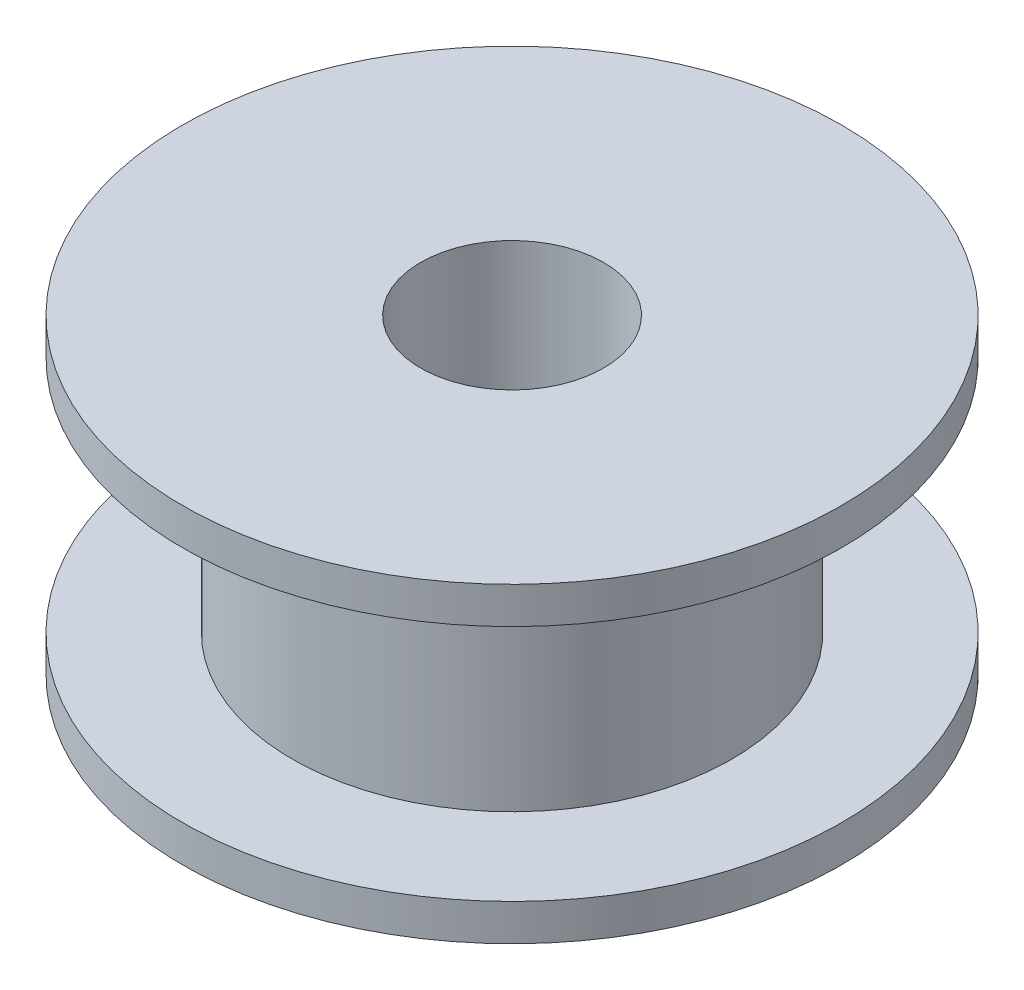
SolidWorks part; units mm, degrees
material "1060 slitina"
ref_plane "Přední rovina" through (0, 0, 0) normal (0, 0, 1) x (1, 0, 0)
ref_plane "Horní rovina" through (0, 0, 0) normal (0, 1, 0) x (1, 0, 0)
ref_plane "Pravá rovina" through (0, 0, 0) normal (1, 0, 0) x (0, 0, -1)
sketch "Skica1" plane through (0, 0, 0) normal (0, 0, 1) x (1, 0, 0)
  line L0 (0, 0) -> (0, 55.9392) construction
  line L1 (-9, 2.2179) -> (-9, 3.2179)
  line L2 (-9, 3.2179) -> (-6, 3.2179)
  line L3 (-6, 3.2179) -> (-6, 9.7179)
  line L4 (-6, 9.7179) -> (-9, 9.7179)
  line L5 (-9, 9.7179) -> (-9, 10.7179)
  line L6 (-9, 10.7179) -> (-2.5, 10.7179)
  line L7 (-2.5, 10.7179) -> (-2.5, 2.2179)
  line L8 (-2.5, 2.2179) -> (-9, 2.2179)
  line L9 (-6, 6.4679) -> (-2.5, 6.4679) construction
  dimension "D1" = 5
  dimension "D2" = 12
  dimension "D3" = 18
  dimension "D4" = 8.5
  dimension "D5" = 6.5
revolve "Rotovat1" add sketch "Skica1" angle 360 about L0
